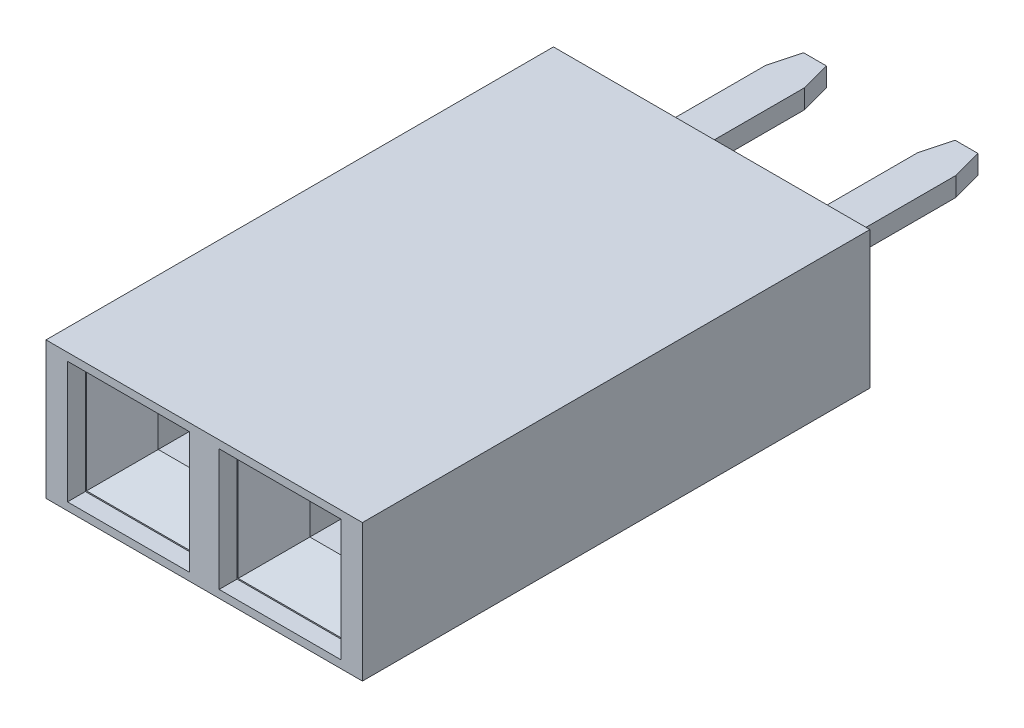
SolidWorks part; units mm, degrees
ref_plane "前视基准面" through (0, 0, 0) normal (0, 0, 1) x (1, 0, 0)
ref_plane "上视基准面" through (0, 0, 0) normal (0, 1, 0) x (1, 0, 0)
ref_plane "右视基准面" through (0, 0, 0) normal (1, 0, 0) x (0, 0, -1)
sketch "草图1" plane through (0, 0, 0) normal (0, 0, 1) x (1, 0, 0)
  line L1 (2.65, -1.15) -> (-2.65, -1.15)
  line L2 (2.65, -1.15) -> (2.65, 1.15)
  line L3 (2.65, 1.15) -> (-2.65, 1.15)
  line L4 (-2.65, -1.15) -> (-2.65, 1.15)
  line L5 (2.65, -1.15) -> (-2.65, 1.15) construction
  line L6 (2.65, 1.15) -> (-2.65, -1.15) construction
  point P0 (0, 0)
  dimension "D1" = 5.3
  dimension "D2" = 2.3
extrude "凸台-拉伸1" add sketch "草图1" along normal mid plane 8.5
sketch "草图2" plane through (0, 0, 4.25) normal (0, 0, 1) x (1, 0, 0)
  line L0 (-1.27, 0) -> (1.27, 0) construction
  line L1 (-0.87, -0.4) -> (-1.67, -0.4)
  line L2 (-0.87, -0.4) -> (-0.87, 0.4)
  line L3 (-0.87, 0.4) -> (-1.67, 0.4)
  line L4 (-1.67, -0.4) -> (-1.67, 0.4)
  line L5 (-0.87, -0.4) -> (-1.67, 0.4) construction
  line L6 (-0.87, 0.4) -> (-1.67, -0.4) construction
  line L7 (1.67, -0.4) -> (0.87, -0.4)
  line L8 (1.67, -0.4) -> (1.67, 0.4)
  line L9 (1.67, 0.4) -> (0.87, 0.4)
  line L10 (0.87, -0.4) -> (0.87, 0.4)
  line L11 (1.67, -0.4) -> (0.87, 0.4) construction
  line L12 (1.67, 0.4) -> (0.87, -0.4) construction
  point P0 (-1.27, 0)
  point P5 (1.27, 0)
  dimension "D1" = 0.8
  dimension "D2" = 2.54
extrude "切除-拉伸1" cut sketch "草图2" against normal blind 8
sketch "草图3" plane through (0, 0, 4.25) normal (0, 0, 1) x (1, 0, 0)
  line L0 (-1.27, 0) -> (-1.27, 0.4) construction
  line L1 (-0.25, -1.02) -> (-2.29, -1.02)
  line L2 (-0.25, -1.02) -> (-0.25, 1.02)
  line L3 (-0.25, 1.02) -> (-2.29, 1.02)
  line L4 (-2.29, -1.02) -> (-2.29, 1.02)
  line L5 (-0.25, -1.02) -> (-2.29, 1.02) construction
  line L6 (-0.25, 1.02) -> (-2.29, -1.02) construction
  line L7 (-0.87, 0.4) -> (-1.67, 0.4) construction
  line L8 (-1.27, 0) -> (-0.87, 0) construction
  line L9 (-0.87, -0.4) -> (-0.87, 0.4) construction
  line L10 (0, 1.15) -> (0, -1.15) construction
  line L11 (2.65, 1.15) -> (-2.65, 1.15) construction
  line L12 (-2.65, -1.15) -> (2.65, -1.15) construction
  line L13 (0.25, 1.02) -> (2.29, 1.02)
  line L14 (2.29, -1.02) -> (2.29, 1.02)
  line L15 (0.25, -1.02) -> (2.29, -1.02)
  line L16 (0.25, -1.02) -> (0.25, 1.02)
  point P0 (-1.27, 0)
  dimension "D1" = 0.5
extrude "切除-拉伸2" cut sketch "草图3" against normal blind 0.3
chamfer "倒角1" distance 0.6 angle 45 8 edges at (0.87, 0, 3.95) (1.27, -0.4, 3.95) (1.67, 0, 3.95) (1.27, 0.4, 3.95) (-1.27, -0.4, 3.95) (-0.87, 0, 3.95) (-1.67, 0, 3.95) (-1.27, 0.4, 3.95)
sketch "草图4" plane through (0, 0, -4.25) normal (0, 0, -1) x (-1, 0, 0)
  line L0 (1.27, 0) -> (-1.27, 0) construction
  line L2 (-0.945, -0.16) -> (-1.595, -0.16)
  line L3 (-0.945, -0.16) -> (-0.945, 0.16)
  line L4 (-0.945, 0.16) -> (-1.595, 0.16)
  line L5 (-1.595, -0.16) -> (-1.595, 0.16)
  line L6 (-0.945, -0.16) -> (-1.595, 0.16) construction
  line L7 (-0.945, 0.16) -> (-1.595, -0.16) construction
  line L8 (1.595, -0.16) -> (0.945, -0.16)
  line L9 (1.595, -0.16) -> (1.595, 0.16)
  line L10 (1.595, 0.16) -> (0.945, 0.16)
  line L11 (0.945, -0.16) -> (0.945, 0.16)
  line L12 (1.595, -0.16) -> (0.945, 0.16) construction
  line L13 (1.595, 0.16) -> (0.945, -0.16) construction
  point P4 (0, 0)
  dimension "D1" = 2.54
  dimension "D2" = 0.32
  dimension "D3" = 0.65
extrude "凸台-拉伸2" add sketch "草图4" along normal blind 3
chamfer "倒角2" distance 0.5 angle 15 4 edges at (-1.595, 0, -7.25) (-0.945, 0, -7.25) (1.595, 0, -7.25) (0.945, 0, -7.25)
